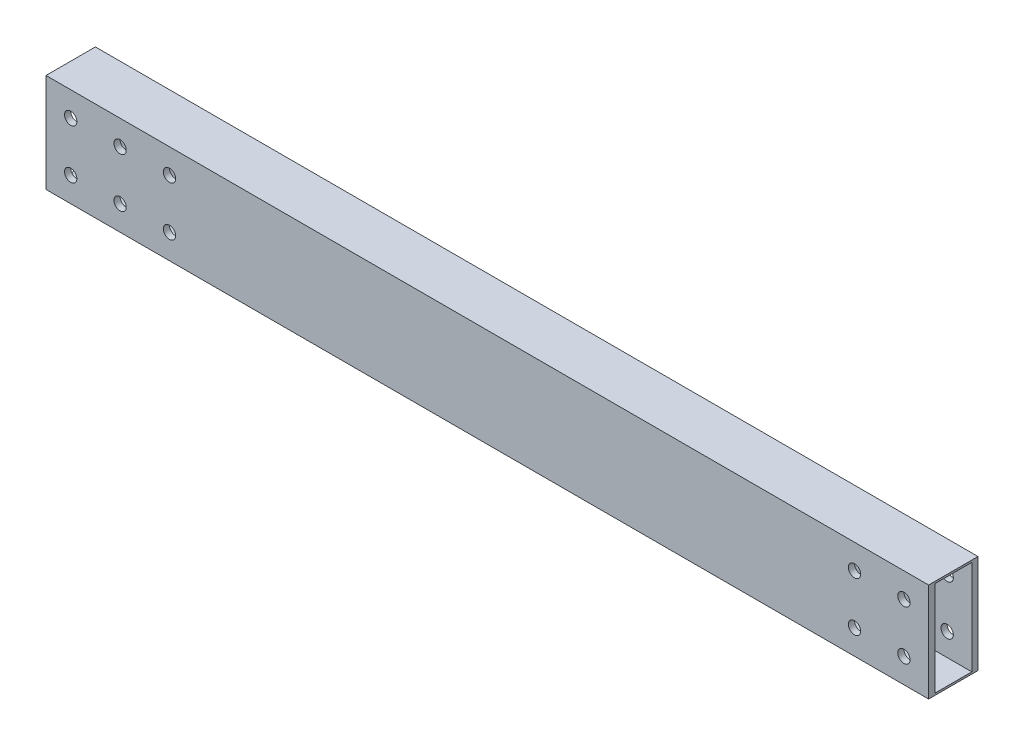
SolidWorks part; units mm, degrees
other "Markup1"
sketch "Sketch6" plane through (0, 0, 0) normal (0, 0, 1) x (1, 0, 0)
ref_plane "Front Plane" through (0, 0, 0) normal (0, 0, 1) x (1, 0, 0)
ref_plane "Top Plane" through (0, 0, 0) normal (0, 1, 0) x (1, 0, 0)
ref_plane "Right Plane" through (0, 0, 0) normal (1, 0, 0) x (0, 0, -1)
sketch "Sketch1" plane through (0, 0, 0) normal (1, 0, 0) x (0, 0, -1)
  line L1 (0, 0) -> (25.4, 0)
  line L2 (0, 0) -> (0, 50.8)
  line L3 (0, 50.8) -> (25.4, 50.8)
  line L4 (25.4, 0) -> (25.4, 50.8)
  dimension "D1" = 50.8
  dimension "D2" = 25.4
extrude "Boss-Extrude1" add sketch "Sketch1" along normal blind 453.9369
sketch "Sketch2" plane through (453.9369, 0, 0) normal (1, 0, 0) x (0, 0, -1)
  line L0 (25.4, 0) -> (25.4, 50.8) construction
  line L1 (3.175, 49.784) -> (22.225, 49.784)
  line L2 (3.175, 49.784) -> (3.175, 1.016)
  line L3 (3.175, 1.016) -> (22.225, 1.016)
  line L4 (22.225, 49.784) -> (22.225, 1.016)
  line L5 (0, 50.8) -> (0, 0) construction
  line L6 (25.4, 50.8) -> (0, 50.8) construction
  line L7 (0, 0) -> (25.4, 0) construction
  dimension "D1" = 3.175
  dimension "D2" = 3.175
  dimension "D3" = 1.016
  dimension "D4" = 1.016
extrude "Cut-Extrude1" cut sketch "Sketch2" against normal through all
sketch "Sketch5" plane through (0, 0, 0) normal (0, 0, 1) x (1, 0, 0)
  line L0 (0, 50.8) -> (0, 0) construction
  line L1 (453.9369, 50.8) -> (0, 50.8) construction
  line L2 (453.9369, 0) -> (0, 0) construction
  line L3 (453.9369, 50.8) -> (453.9369, 0) construction
  circle A0 centre (12.7, 38.1) radius 3.175
  circle A1 centre (38.1, 38.1) radius 3.175
  circle A2 centre (12.7, 12.7) radius 3.175
  circle A3 centre (38.1, 12.7) radius 3.175
  circle A4 centre (63.5, 38.1) radius 3.175
  circle A5 centre (63.5, 12.7) radius 3.175
  circle A6 centre (441.2369, 38.1) radius 3.175
  circle A7 centre (441.2369, 12.7) radius 3.175
  circle A8 centre (415.8369, 38.1) radius 3.175
  circle A9 centre (415.8369, 12.7) radius 3.175
  dimension "D1" = 6.35
  dimension "D2" = 12.7
  dimension "D3" = 12.7
  dimension "D4" = 12.7
  dimension "D5" = 38.1
  dimension "D6" = 25.4
  dimension "D7" = 25.4
  dimension "D8" = 12.7
  dimension "D9" = 25.4
  dimension "D10" = 12.7
  dimension "D11" = 25.4
  dimension "D12" = 25.4
  dimension "D13" = 6.35
  dimension "D14" = 6.35
  dimension "D15" = 25.4
  dimension "D16" = 12.7
  dimension "D18" = 25.4
  dimension "D19" = 12.7
  dimension "D20" = 6.35
  dimension "D24" = 12.7
  dimension "D25" = 6.35
  dimension "D26" = 6.35
  dimension "D17" = 12.7
  dimension "D21" = 12.7
  dimension "D22" = 25.4
  dimension "D23" = 25.4
extrude "Cut-Extrude4" cut sketch "Sketch5" against normal through all both and the other way through all
